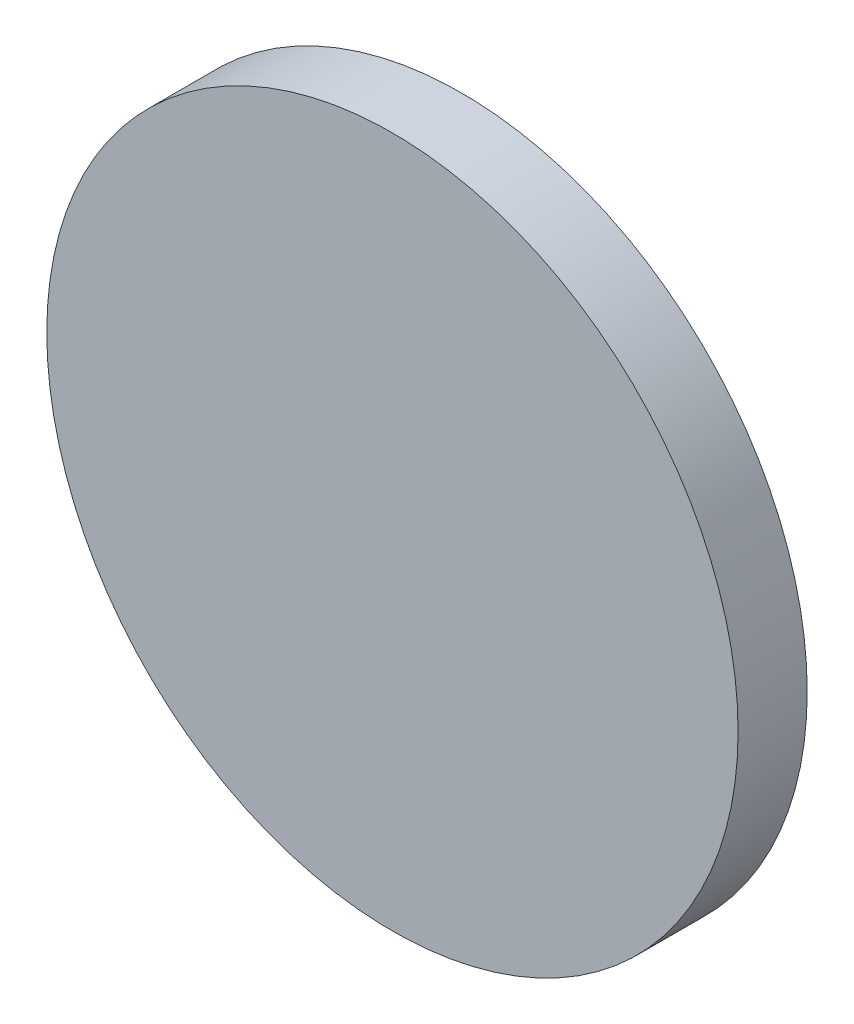
SolidWorks part; units mm, degrees
ref_plane "Front Plane" through (0, 0, 0) normal (0, 0, 1) x (1, 0, 0)
ref_plane "Top Plane" through (0, 0, 0) normal (0, 1, 0) x (1, 0, 0)
ref_plane "Right Plane" through (0, 0, 0) normal (1, 0, 0) x (0, 0, -1)
sketch "Sketch1" plane through (0, 0, 0) normal (0, 0, 1) x (1, 0, 0)
  circle A0 centre (0, 0) radius 12.7
  dimension "D1" = 25.4
extrude "Boss-Extrude1" add sketch "Sketch1" along normal blind 2.54
